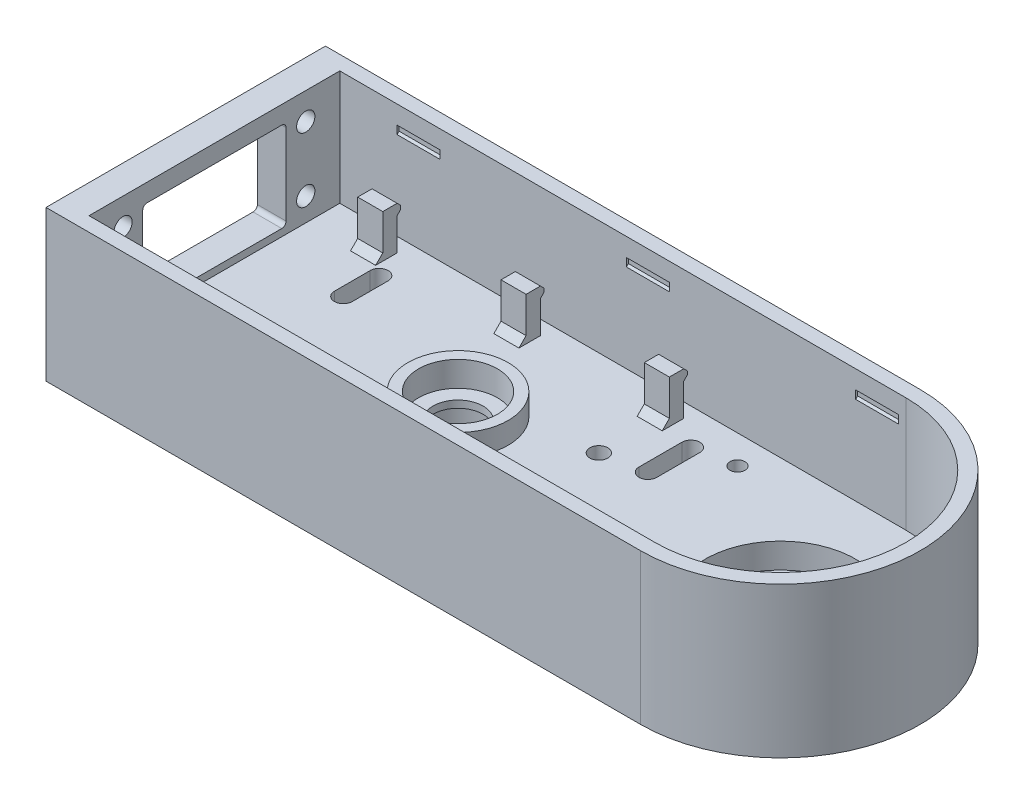
SolidWorks part; units mm, degrees
ref_plane "Front Plane" through (0, 0, 0) normal (0, 0, 1) x (1, 0, 0)
ref_plane "Top Plane" through (0, 0, 0) normal (0, 1, 0) x (1, 0, 0)
ref_plane "Right Plane" through (0, 0, 0) normal (1, 0, 0) x (0, 0, -1)
sketch "Sketch1" plane through (0, 0, 0) normal (0, 1, 0) x (1, 0, 0)
  line L0 (0, 39) -> (-166, 39)
  line L1 (-166, 39) -> (-166, -39)
  line L2 (-166, -39) -> (0, -39)
  arc A0 (0, -39) -> (0, 39) centre (0, 0) ccw
  dimension "D1" = 78
  dimension "D2" = 166
extrude "Boss-Extrude1" add sketch "Sketch1" along normal blind 10
sketch "Sketch2" plane through (0, 10, 0) normal (0, 1, 0) x (1, 0, 0)
  line L0 (0, 35) -> (-158, 35)
  line L2 (-158, -35) -> (0, -35)
  line L3 (0, 39) -> (-166, 39)
  line L4 (-166, 39) -> (-166, -39)
  line L5 (-166, -39) -> (0, -39)
  line L6 (0, 39) -> (-166, 39)
  line L7 (-166, 39) -> (-166, -39)
  line L8 (-166, -39) -> (0, -39)
  line L9 (-158, 35) -> (-158, -35)
  line L10 (0, 35) -> (-162, 35) construction
  line L11 (-162, -35) -> (0, -35) construction
  line L13 (-162, 35) -> (-162, -35) construction
  arc A0 (0, -35) -> (0, 35) centre (0, 0) ccw
  arc A1 (0, -39) -> (0, 39) centre (0, 0) ccw
  arc A2 (0, -39) -> (0, 39) centre (0, 0) ccw
  dimension "D3" = 8
  dimension "D1" = 0
  dimension "D2" = 4
extrude "Boss-Extrude2" add sketch "Sketch2" along normal blind 32 contours L0 L9 L2 A0
sketch "Sketch3" plane through (-166, 0, 0) normal (-1, 0, 0) x (0, 0, 1)
  line L0 (-39, 0) -> (39, 0) construction
  line L1 (-20, 12) -> (20, 12)
  line L2 (-20, 12) -> (-20, 37)
  line L3 (-20, 37) -> (20, 37)
  line L4 (20, 12) -> (20, 37)
  line L5 (-20, 12) -> (20, 37) construction
  line L6 (-20, 37) -> (20, 12) construction
  circle A0 centre (-25.5, 34.5) radius 2.55
  circle A1 centre (-25.5, 16.5) radius 2.55
  circle A2 centre (25.5, 16.5) radius 2.55
  circle A3 centre (25.5, 34.5) radius 2.55
  point P0 (0, 24.5)
  point P16 (0, 0)
  point P17 (0, 0)
  point P18 (0, 0)
  point P19 (0, 0)
  point P20 (0, 0)
  dimension "D5" = 5.1
  dimension "D6" = 5.1
  dimension "D7" = 5.1
  dimension "D8" = 5.1
  dimension "D1" = 25
  dimension "D2" = 40
  dimension "D3" = 12
  dimension "D4" = 16.5
  dimension "D9" = 5.5
  dimension "D10" = 5.5
  dimension "D11" = 18
extrude "Cut-Extrude1" cut sketch "Sketch3" against normal up to next
fillet "Fillet1" radius 1.2 4 edges at (-162, 37, 20) (-162, 12, 20) (-162, 37, -20) (-162, 12, -20)
sketch "Sketch4" plane through (0, 10, 0) normal (0, 1, 0) x (1, 0, 0)
  line L0 (-91.7844, 7.0785) -> (-7.1622, 28.4111) construction
  line L1 (-91.7844, -7.0785) -> (-7.1622, -28.4111) construction
  line L2 (-90, 0) -> (0, 0) construction
  line L3 (-90, 0) -> (-238, 0) construction
  line L4 (-238.8216, 6.2966) -> (-93.2995, 25.2856) construction
  line L5 (-238.8216, -6.2966) -> (-93.2995, -25.2856) construction
  arc A0 (-7.1622, -28.4111) -> (-7.1622, 28.4111) centre (0, 0) ccw construction
  arc A1 (-91.7844, 7.0785) -> (-91.7844, -7.0785) centre (-90, 0) ccw construction
  circle A2 centre (-90, 0) radius 7
  circle A3 centre (0, 0) radius 17.5
  arc A4 (-238.8216, 6.2966) -> (-238.8216, -6.2966) centre (-238, 0) ccw construction
  arc A5 (-93.2995, -25.2856) -> (-93.2995, 25.2856) centre (-90, 0) ccw construction
  dimension "D1" = 58.6
  dimension "D2" = 14.6
  dimension "D4" = 35
  dimension "D5" = 14
  dimension "D7" = 51
  dimension "D8" = 12.7
  dimension "D3" = 90
  dimension "D6" = 148
extrude "Cut-Extrude2" cut sketch "Sketch4" against normal through all
sketch "Sketch5" plane through (0, 10, 0) normal (0, 1, 0) x (1, 0, 0)
  circle A0 centre (0, 0) radius 21
  dimension "D1" = 42
extrude "Cut-Extrude3" cut sketch "Sketch5" against normal blind 7
sketch "Sketch6" plane through (0, 10, 0) normal (0, 1, 0) x (1, 0, 0)
  circle A0 centre (-90, 0) radius 11
  circle A1 centre (-90, 0) radius 14
  dimension "D1" = 22
  dimension "D2" = 3
extrude "Boss-Extrude3" add sketch "Sketch6" along normal blind 6
sketch "Sketch7" plane through (0, 10, 0) normal (0, 1, 0) x (1, 0, 0)
  line L0 (-135, 23) -> (-135, 13) construction
  line L1 (-132.5, 23) -> (-132.5, 13)
  line L2 (-137.5, 23) -> (-137.5, 13)
  line L3 (-135, -13) -> (-135, -23) construction
  line L4 (-132.5, -13) -> (-132.5, -23)
  line L5 (-137.5, -13) -> (-137.5, -23)
  line L6 (-158, 35) -> (-158, -35) construction
  line L7 (0, 35) -> (-158, 35) construction
  line L8 (-158, -35) -> (0, -35) construction
  line L9 (-50, 25) -> (-50, 13) construction
  line L10 (-47.5, 25) -> (-47.5, 13)
  line L11 (-52.5, 25) -> (-52.5, 13)
  line L12 (0, 35) -> (-158, 35) construction
  line L13 (-50, -21) -> (-50, -25) construction
  line L14 (-47.5, -21) -> (-47.5, -25)
  line L15 (-52.5, -21) -> (-52.5, -25)
  arc A0 (-132.5, 23) -> (-137.5, 23) centre (-135, 23) ccw
  arc A1 (-137.5, 13) -> (-132.5, 13) centre (-135, 13) ccw
  arc A2 (-132.5, -13) -> (-137.5, -13) centre (-135, -13) ccw
  arc A3 (-137.5, -23) -> (-132.5, -23) centre (-135, -23) ccw
  arc A4 (-47.5, 25) -> (-52.5, 25) centre (-50, 25) ccw
  arc A5 (-52.5, 13) -> (-47.5, 13) centre (-50, 13) ccw
  arc A6 (-47.5, -21) -> (-52.5, -21) centre (-50, -21) ccw
  arc A7 (-52.5, -25) -> (-47.5, -25) centre (-50, -25) ccw
  point P2 (-135, 18)
  point P7 (-135, -18)
  point P22 (-50, 19)
  point P31 (-50, -23)
  dimension "D1" = 2.5
  dimension "D2" = 2.5
  dimension "D9" = 2.5
  dimension "D12" = 2.5
  dimension "D3" = 23
  dimension "D4" = 10
  dimension "D5" = 12
  dimension "D6" = 12
  dimension "D7" = 10
  dimension "D8" = 108
  dimension "D10" = 10
  dimension "D11" = 12
  dimension "D13" = 4
  dimension "D14" = 10
extrude "Cut-Extrude4" cut sketch "Sketch7" against normal through all
sketch "Sketch8" plane through (0, 0, 0) normal (0, -1, 0) x (1, 0, 0)
  circle A0 centre (-90, 0) radius 11
  dimension "D1" = 22
extrude "Cut-Extrude5" cut sketch "Sketch8" against normal blind 7
sketch "Sketch9" plane through (0, 10, 0) normal (0, 1, 0) x (1, 0, 0)
  line L0 (0, 35) -> (-158, 35) construction
  line L1 (-158, 35) -> (-158, -35) construction
  line L2 (-158, -35) -> (0, -35) construction
  line L3 (-58, -9.46) -> (-49.612, -5) construction
  line L4 (-158, -35) -> (0, -35) construction
  circle A0 centre (-39, 27) radius 2.1
  arc A1 (-47.5, 25) -> (-52.5, 25) centre (-50, 25) ccw construction
  circle A2 centre (-61.5, 10.8097) radius 2.5
  arc A3 (-52.5, 13) -> (-47.5, 13) centre (-50, 13) ccw construction
  circle A4 centre (-58, -9.46) radius 1.6
  circle A5 centre (-49.612, -5) radius 1.6
  dimension "D1" = 8
  dimension "D2" = 11
  dimension "D3" = 4.2
  dimension "D6" = 5
  dimension "D9" = 3.2
  dimension "D10" = 3.2
  dimension "D4" = 24.1903
  dimension "D5" = 11.5
  dimension "D7" = 100
  dimension "D8" = 9.5
  dimension "D11" = 30
  dimension "D12" = 28
extrude "Cut-Extrude6" cut sketch "Sketch9" against normal through all
ref_plane "Plane1" through (-145, 0, 0) normal (1, 0, 0) x (0, 0, -1)
sketch "Sketch10" plane through (-145, 0, 0) normal (1, 0, 0) x (0, 0, -1)
  line L0 (31, 10) -> (31, 19)
  line L1 (35, 10) -> (-35, 10) construction
  line L2 (31, 19) -> (32, 20)
  line L3 (32, 20) -> (32, 21)
  line L4 (32, 21) -> (31, 22)
  line L5 (31, 22) -> (27, 22)
  line L6 (27, 22) -> (27, 10)
  line L8 (35, 10) -> (-35, 10)
  line L9 (35, 42) -> (35, 10) construction
  point P6 (25.4546, 11.0594)
  point P10 (0, 0)
  dimension "D1" = 4
  dimension "D2" = 4
  dimension "D3" = 3
  dimension "D4" = 4
  dimension "D5" = 135
  dimension "D6" = 135
  dimension "D7" = 1
  dimension "D8" = 12
extrude "Boss-Extrude4" add sketch "Sketch10" along normal blind 7 contours L8 L0 L2 L3 L4 L5 L6
chamfer "Chamfer1" distance 2 angle 45 1 edges at (-141.5, 10, -27)
pattern_linear "LPattern1" count 3 spacing 40 along (1, 0, 0) of "Boss-Extrude4", "Chamfer1"
ref_plane "Plane2" through (-142, 0, 0) normal (-1, 0, 0) x (0, 0, 1)
sketch "Sketch11" plane through (-142, 0, 0) normal (-1, 0, 0) x (0, 0, 1)
  line L7 (-35, 42) -> (-35, 10) construction
  line L8 (-35, 42) -> (-35, 10)
  line L19 (-35, 42) -> (35, 42) construction
  line L20 (-35, 42) -> (35, 42)
  line L21 (-34.4, 42) -> (-34.4, 37.5)
  line L22 (-34.4, 37.5) -> (-35.55, 36.35)
  line L23 (-35.55, 36.35) -> (-35.55, 35.15)
  line L24 (-35.55, 35.15) -> (-34.4, 34)
  line L25 (-34.4, 34) -> (-30.9, 34)
  line L26 (-30.9, 34) -> (-30.9, 42)
  line L27 (-39, 42) -> (-39, 0) construction
  point P30 (-34.3461, 35.9863)
  dimension "D7" = 3.5
  dimension "D8" = 3.5
  dimension "D9" = 1.2
  dimension "D10" = 135
  dimension "D11" = 135
  dimension "D12" = 8
  dimension "D13" = 4.5
  dimension "D14" = 4.6
extrude "Cut-Extrude7" cut sketch "Sketch11" against normal blind 12 contours L23 L24 L8 L22
pattern_linear "LPattern2" count 3 spacing 64 along (1, 0, 0) of "Cut-Extrude7"
mirror "Mirror1" about plane through (0, 0, 0) normal (0, 0, 1) of "LPattern2", "Cut-Extrude7"
sketch "Sketch12" plane through (0, 0, 0) normal (0, 0, 1) x (1, 0, 0)
  line L0 (39, 42) -> (0, 42) construction
  line L1 (39, 42) -> (0, 42)
  line L2 (34.4, 42) -> (34.4, 37.5)
  line L3 (34.4, 37.5) -> (35.55, 36.35)
  line L4 (35.55, 36.35) -> (35.55, 35.15)
  line L5 (35.55, 35.15) -> (34.4, 34)
  line L6 (34.4, 34) -> (30.9, 34)
  line L7 (30.9, 34) -> (30.9, 42)
  line L8 (35, 42) -> (35, 32.2725)
  line L9 (0, 42) -> (0, 38.3259)
  dimension "D1" = 3.5
  dimension "D2" = 3.5
  dimension "D3" = 8
  dimension "D4" = 135
  dimension "D5" = 1.2
  dimension "D6" = 4.5
  dimension "D7" = 4.6
  dimension "D8" = 4
revolve "Cut-Revolve1" cut sketch "Sketch12" angle 20 mid plane about L9
sketch "Sketch13" plane through (0, 10, 0) normal (0, 1, 0) x (1, 0, 0)
  circle A1 centre (-90, 0) radius 11
  circle A2 centre (-90, 0) radius 11
  dimension "D1" = 0
extrude "Cut-Extrude8" cut sketch "Sketch13" against normal blind 1
